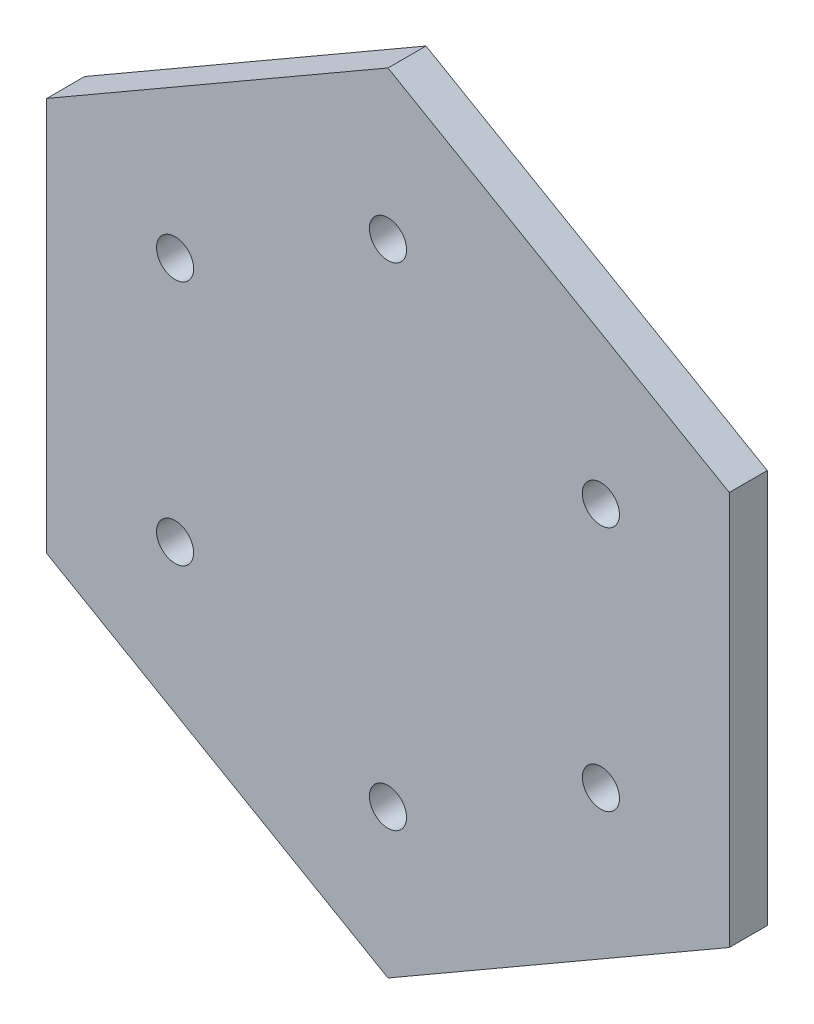
SolidWorks part; units mm, degrees
ref_plane "Front Plane" through (0, 0, 0) normal (1, 0, 0) x (0, 1, 0)
ref_plane "Top Plane" through (0, 0, 0) normal (0, 0, 1) x (0, 1, 0)
ref_plane "Right Plane" through (0, 0, 0) normal (0, 1, 0) x (-1, 0, 0)
sketch "Sketch2" plane through (0, 0, 0) normal (0, 0, 1) x (0, 1, 0)
  line L0 (0, 28.5) -> (0, -28.5) construction
  line L1 (16.4545, -28.5) -> (32.909, 0)
  line L2 (32.909, 0) -> (16.4545, 28.5)
  line L3 (16.4545, 28.5) -> (-16.4545, 28.5)
  line L4 (-16.4545, 28.5) -> (-32.909, 0)
  line L5 (-32.909, 0) -> (-16.4545, -28.5)
  line L6 (-16.4545, -28.5) -> (16.4545, -28.5)
  line L7 (14.7224, -25.5) -> (29.4449, 0) construction
  line L8 (29.4449, 0) -> (14.7224, 25.5) construction
  line L9 (14.7224, 25.5) -> (-14.7224, 25.5) construction
  line L10 (-14.7224, 25.5) -> (-29.4449, 0) construction
  line L11 (-29.4449, 0) -> (-14.7224, -25.5) construction
  line L12 (-14.7224, -25.5) -> (14.7224, -25.5) construction
  circle A0 centre (0, 0) radius 28.5 construction
  circle A1 centre (0, 0) radius 25.5 construction
  circle A2 centre (10.2654, 17.7802) radius 1.55
  circle A3 centre (20.5308, 0) radius 1.55
  circle A4 centre (10.2654, -17.7802) radius 1.55
  circle A5 centre (-10.2654, -17.7802) radius 1.55
  circle A6 centre (-20.5308, 0) radius 1.55
  circle A7 centre (10.2654, 17.7802) radius 7.7198 construction
  circle A8 centre (20.5308, 0) radius 7.7198 construction
  circle A9 centre (10.2654, -17.7802) radius 7.7198 construction
  circle A10 centre (-10.2654, -17.7802) radius 7.7198 construction
  circle A11 centre (-20.5308, 0) radius 7.7198 construction
  circle A12 centre (-10.2654, 17.7802) radius 1.55
  circle A13 centre (-10.2654, 17.7802) radius 7.7198 construction
  dimension "D3" = 3.1
  dimension "D4" = 57
  dimension "D5" = 7.7198
  dimension "D6" = 20.5308
  dimension "D1" = 3
  dimension "D2" = 51
extrude "Boss-Extrude1" add sketch "Sketch2" along normal blind 3.175
